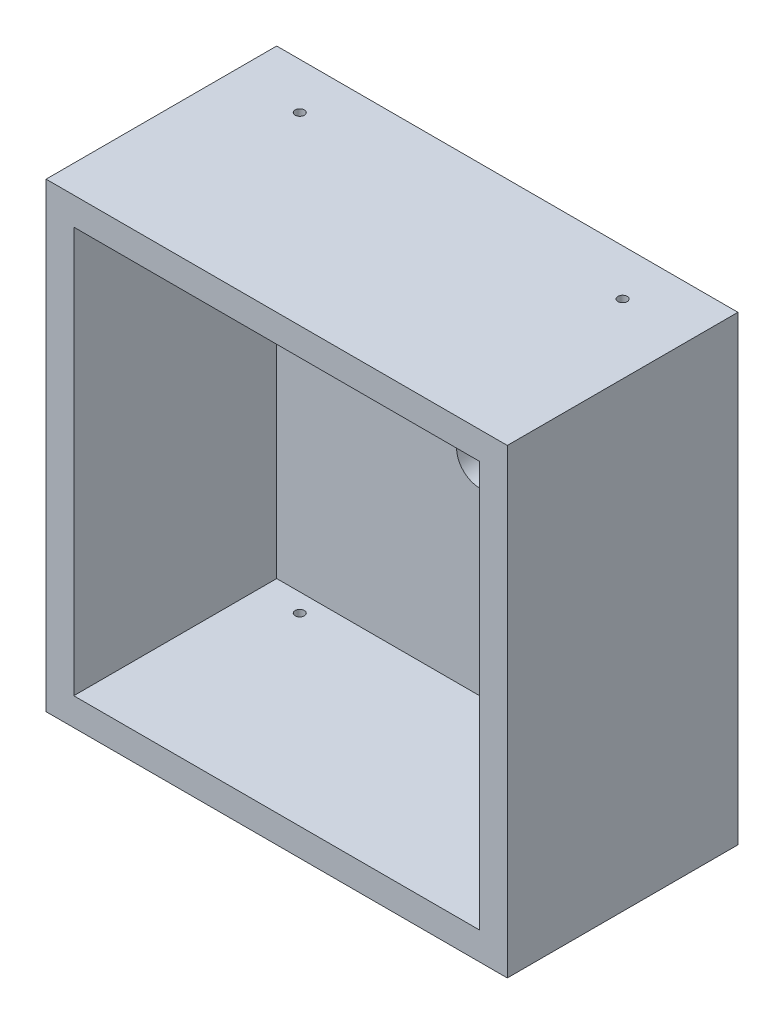
SolidWorks part; units mm, degrees
ref_plane "Plan de face" through (0, 0, 0) normal (0, 0, 1) x (1, 0, 0)
ref_plane "Plan de dessus" through (0, 0, 0) normal (0, 1, 0) x (1, 0, 0)
ref_plane "Plan de droite" through (0, 0, 0) normal (1, 0, 0) x (0, 0, -1)
sketch "Esquisse1" plane through (0, 0, 0) normal (0, 0, 1) x (1, 0, 0)
  line L1 (-44, 44) -> (44, 44)
  line L2 (-44, 44) -> (-44, -44)
  line L3 (-44, -44) -> (44, -44)
  line L4 (44, 44) -> (44, -44)
  dimension "D1" = 88
  dimension "D2" = 88
  dimension "D3" = 44
  dimension "D4" = 44
extrude "Boss.-Extru.1" add sketch "Esquisse1" along normal blind 6
sketch "Esquisse2" plane through (0, 0, 6) normal (0, 0, 1) x (1, 0, 0)
  circle A0 centre (0, 0) radius 5
  dimension "D1" = 10
extrude "Enlèv. mat.-Extru.1" cut sketch "Esquisse2" against normal blind 6
sketch "Esquisse3" plane through (0, -44, 0) normal (0, -1, 0) x (-1, 0, 0)
  line L0 (44, 0) -> (-44, 0)
  line L1 (44, 0) -> (44, -50)
  line L2 (-44, 0) -> (-44, -50)
  line L3 (44, -50) -> (-44, -50)
  dimension "D1" = 50
extrude "Boss.-Extru.2" add sketch "Esquisse3" along normal blind 6
sketch "Esquisse4" plane through (-44, 0, 0) normal (-1, 0, 0) x (0, 0, 1)
  line L0 (0, 44) -> (0, -50)
  line L1 (0, 44) -> (50, 44)
  line L2 (0, -50) -> (50, -50)
  line L3 (50, 44) -> (50, -50)
  line L4 (50, -50) -> (50, -44) construction
extrude "Boss.-Extru.3" add sketch "Esquisse4" along normal blind 6
sketch "Esquisse5" plane through (44, 0, 0) normal (1, 0, 0) x (0, 0, -1)
  line L0 (0, 44) -> (0, -50)
  line L1 (0, 44) -> (-50, 44)
  line L2 (0, -50) -> (-50, -50)
  line L3 (-50, 44) -> (-50, -50)
extrude "Boss.-Extru.4" add sketch "Esquisse5" along normal blind 6
sketch "Esquisse6" plane through (0, 44, 0) normal (0, 1, 0) x (1, 0, 0)
  line L0 (50, 0) -> (-50, 0)
  line L1 (50, 0) -> (50, -50)
  line L2 (-50, 0) -> (-50, -50)
  line L3 (50, -50) -> (-50, -50)
extrude "Boss.-Extru.5" add sketch "Esquisse6" along normal blind 6
sketch "Esquisse7" plane through (0, 50, 0) normal (0, 1, 0) x (1, 0, 0)
  line L0 (62.9405, -10) -> (-77.6197, -10) construction
  line L1 (50, 0) -> (-50, 0) construction
  line L2 (50, -50) -> (50, 0) construction
  line L3 (-50, 0) -> (-50, -50) construction
  circle A0 centre (35, -10) radius 1
  circle A1 centre (-35, -10) radius 1
  dimension "D2" = 2
  dimension "D3" = 2
  dimension "D4" = 15
  dimension "D5" = 15
  dimension "D1" = 10
extrude "Enlèv. mat.-Extru.2" cut sketch "Esquisse7" against normal blind 100
